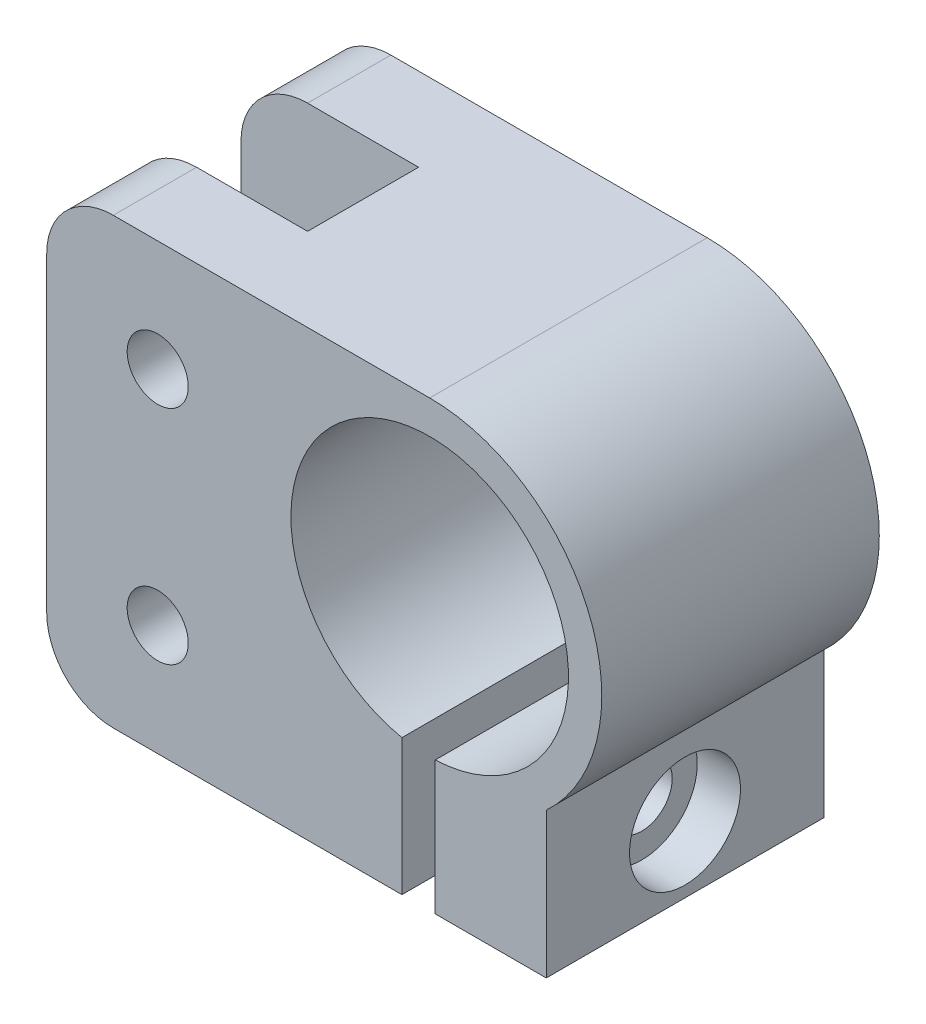
SolidWorks part; units mm, degrees
material "Alumina"
ref_plane "Plano frontal" through (0, 0, 0) normal (0, 0, 1) x (1, 0, 0)
ref_plane "Plano superior" through (0, 0, 0) normal (0, 1, 0) x (1, 0, 0)
ref_plane "Plano direito" through (0, 0, 0) normal (1, 0, 0) x (0, 0, -1)
sketch "Esboço1" plane through (0, 0, 0) normal (0, 0, 1) x (1, 0, 0)
  line L1 (12, 20) -> (-22.5, 20)
  line L2 (22.5, -6.9018) -> (22.5, -20)
  line L3 (22.5, -20) -> (-22.5, -20)
  line L4 (-22.5, 20) -> (-22.5, -20)
  line L5 (22.5, 20) -> (-22.5, -20) construction
  line L6 (22.5, -20) -> (-22.5, 20) construction
  arc A1 (22.5, -6.9018) -> (12, 20) centre (12, 4.5) ccw
  point P0 (0, 0)
  dimension "D3" = 19
  dimension "D4" = 31
  dimension "D1" = 40
  dimension "D2" = 45
  dimension "D5" = 20
extrude "Ressalto-extrusão1" add sketch "Esboço1" along normal mid plane 25
sketch "Esboço2" plane through (0, 20, 0) normal (0, 1, 0) x (1, 0, 0)
  line L0 (-22.5, -12.5) -> (-22.5, 12.5) construction
  line L1 (-22.5, 5) -> (-6.5, 5)
  line L2 (-22.5, 5) -> (-22.5, -5)
  line L3 (-22.5, -5) -> (-6.5, -5)
  line L4 (-6.5, 5) -> (-6.5, -5)
  dimension "D1" = 16
  dimension "D2" = 10
  dimension "D3" = 5
extrude "Corte-extrusão1" cut sketch "Esboço2" against normal through all
fillet "Filete1" radius 6 4 edges at (-22.5, 20, -8.75) (-22.5, 20, 8.75) (-22.5, -20, 8.75) (-22.5, -20, -8.75)
sketch "Esboço5" plane through (0, 0, 12.5) normal (0, 0, 1) x (1, 0, 0)
  circle A0 centre (12, 4.5) radius 12.5
  arc A1 (22.5, -6.9018) -> (12, 20) centre (12, 4.5) ccw construction
  dimension "D1" = 3
extrude "Corte-extrusão2" cut sketch "Esboço5" against normal through all
sketch "Esboço7" plane through (0, 0, -12.5) normal (0, 0, -1) x (-1, 0, 0)
  line L0 (16.5, -20) -> (-22.5, -20) construction
  line L1 (-12.5, -20) -> (-9.5, -20)
  line L2 (-12.5, -20) -> (-12.5, -5)
  line L3 (-12.5, -5) -> (-9.5, -5)
  line L4 (-9.5, -20) -> (-9.5, -5)
  line L5 (-22.5, -20) -> (-22.5, -6.9018) construction
  dimension "D1" = 3
  dimension "D2" = 10
  dimension "D3" = 15
extrude "Corte-extrusão3" cut sketch "Esboço7" against normal through all
hole_wizard "Rebaixo para parafuso Allen sextavado de M51" positions "Esboço8" profile "Esboço9" counterbore size "M5" standard "DIN"
sketch "Esboço8" plane through (22.5, 0, 0) normal (1, 0, 0) x (0, 0, -1)
  line L0 (-12.5, -20) -> (12.5, -20) construction
  point P0 (0, -14)
  dimension "D1" = 6
sketch "Esboço9" plane through (22.5, -14, 0) normal (0, 1, 0) x (0, 0, -1)
  line L0 (0, 0) -> (0, 28.6524)
  line L1 (0, 28.6524) -> (2.75, 27)
  line L2 (2.75, 27) -> (2.75, 3.9)
  line L3 (2.75, 3.9) -> (5, 3.9)
  line L4 (5, 3.9) -> (5, 0)
  line L5 (5, 0) -> (0, 0)
  line L10 (0, 28.6524) -> (-2.75, 27) construction
  line L11 (0, -6.35) -> (0, 107.95) construction
  dimension "Hole Dia." = 5.5
  dimension "Hole Depth" = 27
  dimension "C'Bore Dia." = 10
  dimension "C'Bore Depth" = 3.9
  dimension "Drill Angle" = 118
hole_wizard "Rebaixo para parafuso Allen sextavado de M52" positions "Esboço10" profile "Esboço11" counterbore size "M5" standard "DIN"
sketch "Esboço10" plane through (0, 0, -12.5) normal (0, 0, -1) x (-1, 0, 0)
  line L0 (-12, 20) -> (16.5, 20) construction
  line L1 (22.5, 14) -> (22.5, -14) construction
  point P0 (12.5, 10)
  point P2 (12.5, -10)
  dimension "D1" = 10
  dimension "D2" = 20
  dimension "D3" = 10
sketch "Esboço11" plane through (-12.5, 10, -12.5) normal (1, 0, 0) x (0, 1, 0)
  line L0 (0, 0) -> (0, 28.6524)
  line L1 (0, 28.6524) -> (2.75, 27)
  line L2 (2.75, 27) -> (2.75, 3.9)
  line L3 (2.75, 3.9) -> (5, 3.9)
  line L4 (5, 3.9) -> (5, 0)
  line L5 (5, 0) -> (0, 0)
  line L10 (0, 28.6524) -> (-2.75, 27) construction
  line L11 (0, -6.35) -> (0, 107.95) construction
  dimension "Hole Dia." = 5.5
  dimension "Hole Depth" = 27
  dimension "C'Bore Dia." = 10
  dimension "C'Bore Depth" = 3.9
  dimension "Drill Angle" = 118
